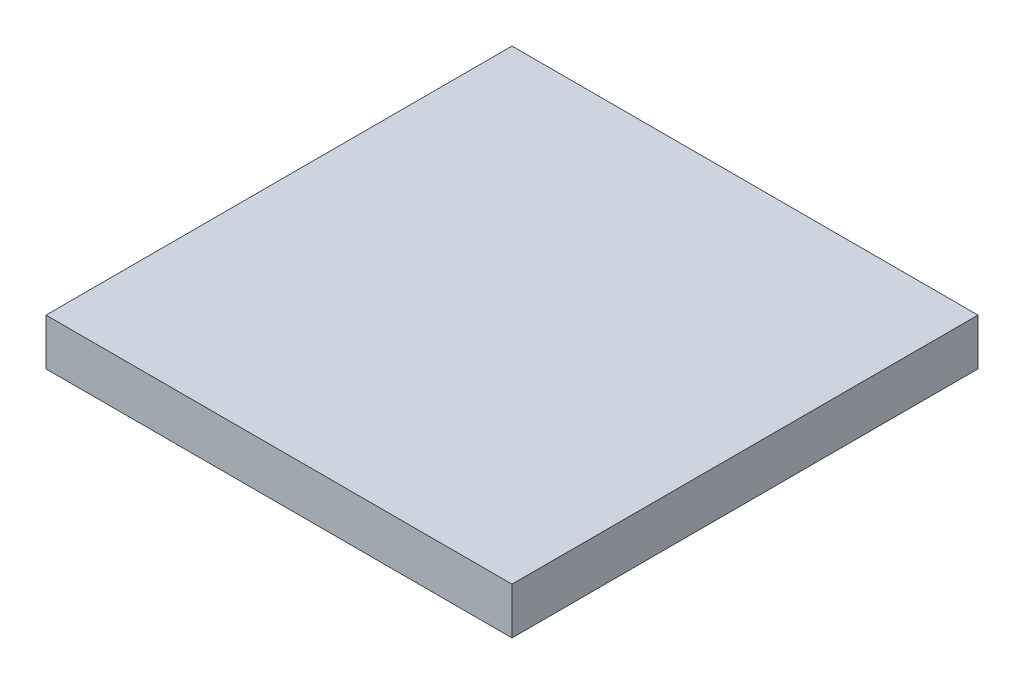
SolidWorks part; units mm, degrees
ref_plane "前视基准面" through (0, 0, 0) normal (0, 0, 1) x (1, 0, 0)
ref_plane "上视基准面" through (0, 0, 0) normal (0, 1, 0) x (1, 0, 0)
ref_plane "右视基准面" through (0, 0, 0) normal (1, 0, 0) x (0, 0, -1)
other "Configuration Table"
sketch "草图1" plane through (0, 0, 0) normal (0, 0, 1) x (1, 0, 0)
  line L0 (-5, 0) -> (5, 0)
extrude "AutoFilletThin" add sketch "草图1" along normal blind 10 thin
